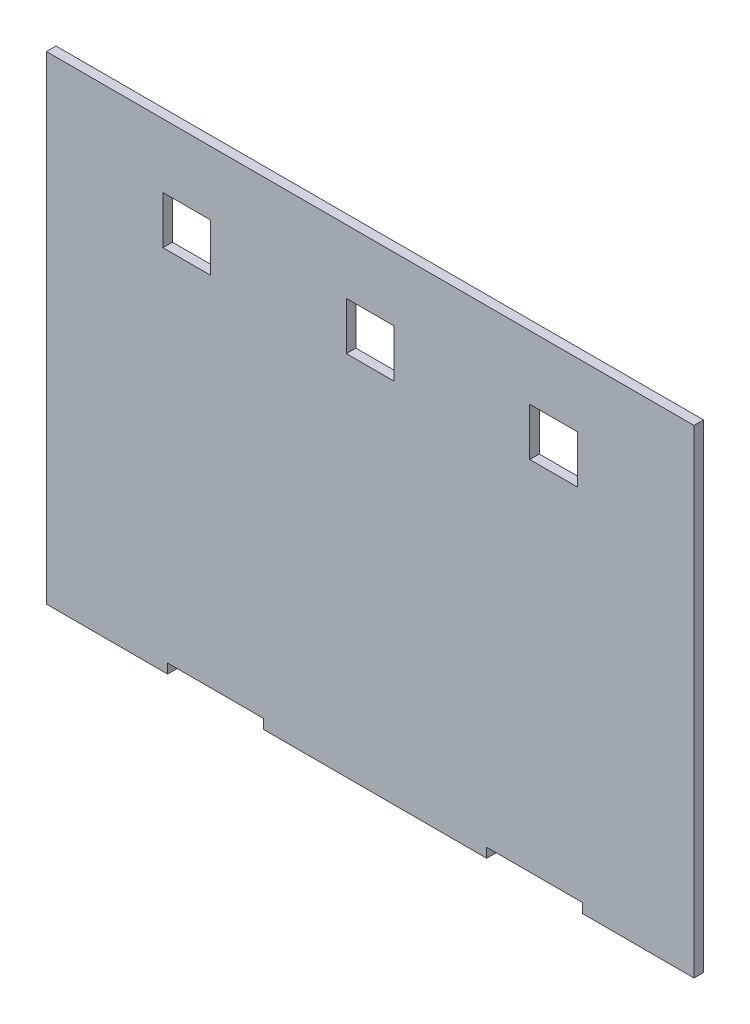
SolidWorks part; units mm, degrees
ref_plane "Front Plane" through (0, 0, 0) normal (0, 0, 1) x (1, 0, 0)
ref_plane "Top Plane" through (0, 0, 0) normal (0, 1, 0) x (1, 0, 0)
ref_plane "Right Plane" through (0, 0, 0) normal (1, 0, 0) x (0, 0, -1)
sketch "Sketch1" plane through (0, 0, 0) normal (0, 0, 1) x (1, 0, 0)
  line L1 (-101.5, 75) -> (101.5, 75)
  line L2 (-101.5, 75) -> (-101.5, -75)
  line L3 (-101.5, -75) -> (101.5, -75)
  line L4 (101.5, 75) -> (101.5, -75)
  line L5 (-101.5, 75) -> (101.5, -75) construction
  line L6 (-101.5, -75) -> (101.5, 75) construction
  point P0 (0, 0)
  dimension "D1" = 150
  dimension "D2" = 203
extrude "Boss-Extrude1" add sketch "Sketch1" along normal blind 3
sketch "Sketch2" plane through (0, 0, 3) normal (0, 0, 1) x (1, 0, 0)
  line L0 (0, 0) -> (0, 105.2664) construction
  line L1 (101.5, 75) -> (-101.5, 75) construction
  line L2 (-65, 55) -> (-50, 55)
  line L3 (-65, 55) -> (-65, 40)
  line L4 (-65, 40) -> (-50, 40)
  line L5 (-50, 55) -> (-50, 40)
  line L6 (65, 40) -> (50, 40)
  line L7 (50, 55) -> (50, 40)
  line L8 (65, 55) -> (50, 55)
  line L9 (65, 55) -> (65, 40)
  line L11 (-7.5, 55) -> (7.5, 55)
  line L12 (-7.5, 55) -> (-7.5, 40)
  line L13 (-7.5, 40) -> (7.5, 40)
  line L14 (7.5, 55) -> (7.5, 40)
  line L15 (-7.5, 55) -> (7.5, 40) construction
  line L16 (-7.5, 40) -> (7.5, 55) construction
  point P7 (-57.5, 55)
  point P14 (0, 47.5)
  dimension "D1" = 15
  dimension "D2" = 15
  dimension "D3" = 50
  dimension "D4" = 20
  dimension "D5" = 15
  dimension "D6" = 15
  dimension "D7" = 20
extrude "Cut-Extrude1" cut sketch "Sketch2" against normal through all
sketch "Sketch3" plane through (0, 0, 3) normal (0, 0, 1) x (1, 0, 0)
  line L0 (-101.5, -75) -> (101.5, -75) construction
  line L1 (-63.5, -75) -> (-33.5, -75)
  line L2 (-63.5, -75) -> (-63.5, -72)
  line L3 (-63.5, -72) -> (-33.5, -72)
  line L4 (-33.5, -75) -> (-33.5, -72)
  line L5 (-48.5, -72) -> (-48.5, -75) construction
  line L6 (-101.5, 75) -> (-101.5, -75) construction
  line L7 (36.5, -75) -> (36.5, -72)
  line L8 (36.5, -75) -> (66.5, -75)
  line L9 (66.5, -75) -> (66.5, -72)
  line L10 (36.5, -72) -> (66.5, -72)
  dimension "D1" = 30
  dimension "D2" = 3
  dimension "D3" = 53
  dimension "D4" = 2
extrude "Cut-Extrude2" cut sketch "Sketch3" against normal blind 10
